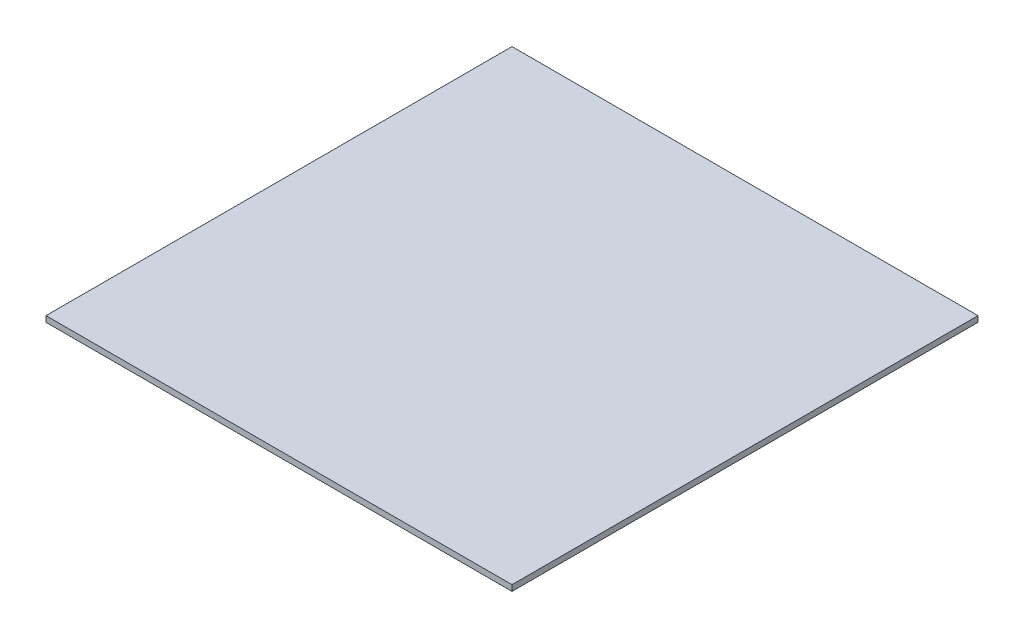
SolidWorks part; units mm, degrees
ref_plane "Front Plane" through (0, 0, 0) normal (0, 0, 1) x (1, 0, 0)
ref_plane "Top Plane" through (0, 0, 0) normal (0, 1, 0) x (1, 0, 0)
ref_plane "Right Plane" through (0, 0, 0) normal (1, 0, 0) x (0, 0, -1)
sketch "Sketch1" plane through (0, 0, 0) normal (0, 1, 0) x (1, 0, 0)
  line L1 (-200, -200) -> (200, -200)
  line L2 (-200, -200) -> (-200, 200)
  line L3 (-200, 200) -> (200, 200)
  line L4 (200, -200) -> (200, 200)
  line L5 (-200, -200) -> (200, 200) construction
  line L6 (-200, 200) -> (200, -200) construction
  point P0 (0, 0)
  dimension "D1" = 400
  dimension "D2" = 400
extrude "Boss-Extrude1" add sketch "Sketch1" along normal blind 5
